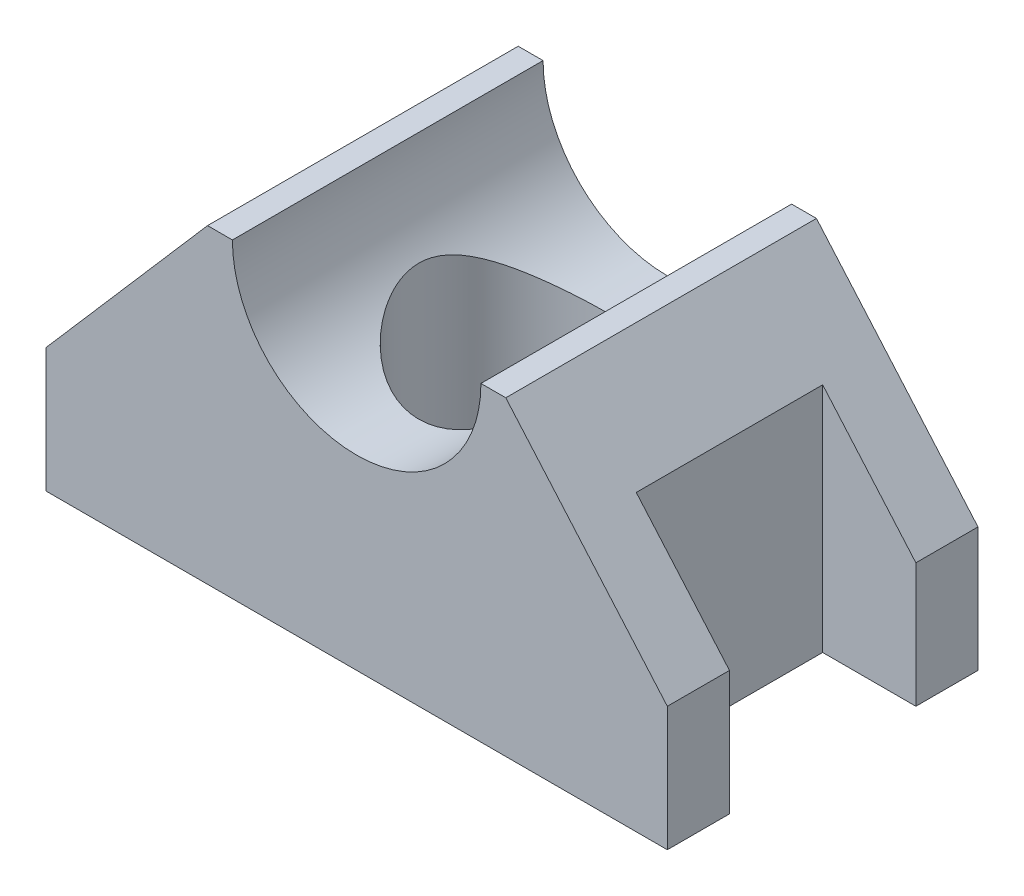
SolidWorks part; units mm, degrees
ref_plane "Front Plane" through (0, 0, 0) normal (0, 0, 1) x (1, 0, 0)
ref_plane "Top Plane" through (0, 0, 0) normal (0, 1, 0) x (1, 0, 0)
ref_plane "Right Plane" through (0, 0, 0) normal (1, 0, 0) x (0, 0, -1)
sketch "Sketch1" plane through (0, 0, 0) normal (0, 0, 1) x (1, 0, 0)
  line L0 (-68.1528, 0) -> (-68.1528, 20)
  line L1 (-68.1528, 20) -> (-42.1528, 50)
  line L2 (-42.1528, 50) -> (-38.1528, 50)
  line L3 (-68.1528, 0) -> (31.8472, 0)
  line L4 (31.8472, 0) -> (31.8472, 20)
  line L5 (31.8472, 20) -> (5.8472, 50)
  line L6 (5.8472, 50) -> (1.8472, 50)
  arc A0 (-38.1528, 50) -> (1.8472, 50) centre (-18.1528, 50) ccw
  dimension "D6" = 20
  dimension "D1" = 100
  dimension "D2" = 50
  dimension "D3" = 50
  dimension "D4" = 20
  dimension "D5" = 48
extrude "Boss-Extrude1" add sketch "Sketch1" against normal blind 50
sketch "Sketch2" plane through (0, 50, 0) normal (0, 1, 0) x (1, 0, 0)
  circle A0 centre (-18.1528, 25) radius 15
extrude "Cut-Extrude1" cut sketch "Sketch2" against normal blind 50
ref_plane "Plane1" through (0, 0, -10) normal (0, 0, 1) x (1, 0, 0)
sketch "Sketch3" plane through (0, 0, -10) normal (0, 0, 1) x (1, 0, 0)
  line L0 (31.8472, 0) -> (31.8472, 20)
  line L1 (31.8472, 20) -> (16.8472, 37.3077)
  line L2 (31.8472, 20) -> (5.8472, 50) construction
  line L3 (16.8472, 37.3077) -> (16.8472, 0)
  line L4 (-68.1528, 0) -> (31.8472, 0) construction
  line L5 (16.8472, 0) -> (31.8472, 0)
  line L6 (-68.1528, 0) -> (-68.1528, 20)
  line L7 (-68.1528, 20) -> (-53.1528, 37.3077)
  line L8 (-42.1528, 50) -> (-68.1528, 20) construction
  line L9 (-53.1528, 37.3077) -> (-53.1528, 0)
  line L10 (-53.1528, 0) -> (-68.1528, 0)
  dimension "D1" = 15
  dimension "D2" = 15
extrude "Cut-Extrude2" cut sketch "Sketch3" against normal blind 30
